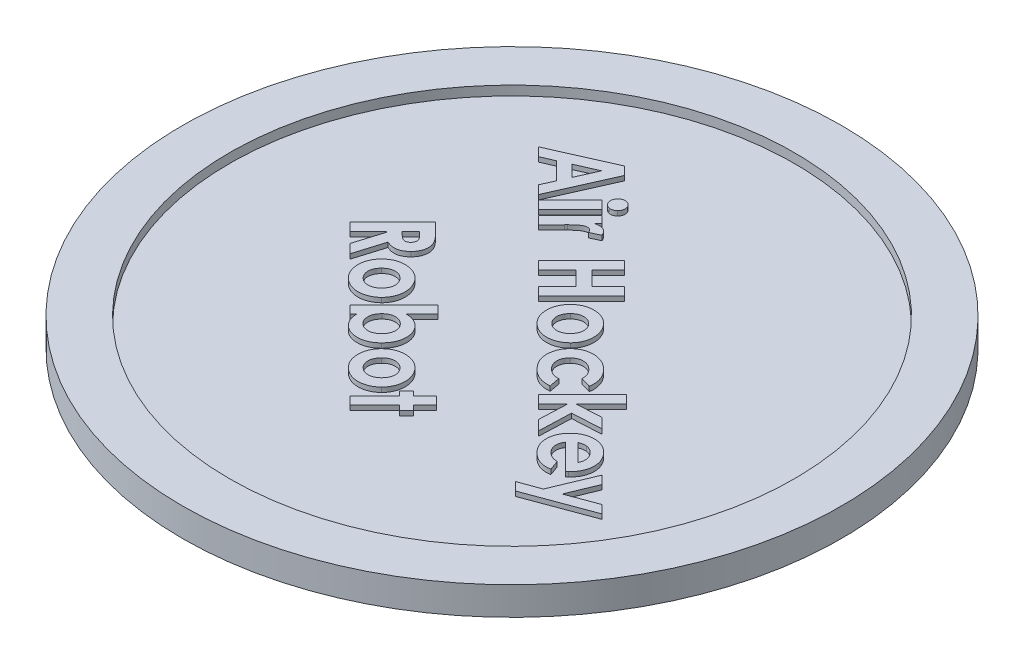
SolidWorks part; units mm, degrees
ref_plane "前基準面" through (0, 0, 0) normal (0, 0, 1) x (1, 0, 0)
ref_plane "上基準面" through (0, 0, 0) normal (0, 1, 0) x (1, 0, 0)
ref_plane "右基準面" through (0, 0, 0) normal (1, 0, 0) x (0, 0, -1)
sketch "草圖1" plane through (0, 0, 0) normal (0, 1, 0) x (1, 0, 0)
  circle A0 centre (0, 0) radius 35
  dimension "D1" = 70
extrude "填料-伸長1" add sketch "草圖1" along normal blind 3 contours A0
sketch "草圖2" plane through (0, 3, 0) normal (0, 1, 0) x (1, 0, 0)
  circle A0 centre (0, 0) radius 30
  dimension "D1" = 60
extrude "除料-伸長1" cut sketch "草圖2" against normal blind 1
sketch "草圖3" plane through (0, 2, 0) normal (0, 1, 0) x (1, 0, 0)
  line L0 (-14.7626, 17.591) -> (16.124, -13.2956) construction
  line L1 (0, 0) -> (1.4142, 1.4142) construction
  text T0 "<b>Air Hockey</b>\r\n<b>Robot</b>" font "Century Gothic" height 6.5
  dimension "D1" = 2
extrude "填料-伸長2" add sketch "草圖3" along normal blind 0.5
